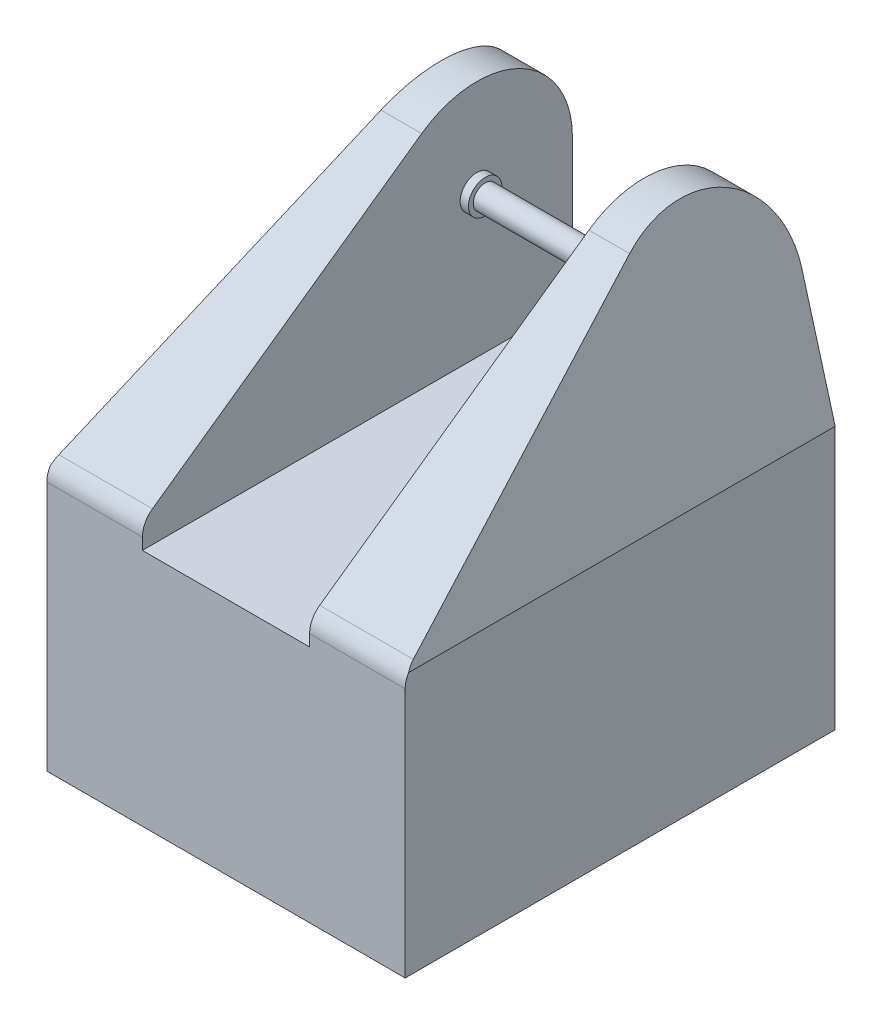
SolidWorks part; units mm, degrees
ref_plane "前基準面" through (0, 0, 0) normal (0, 0, 1) x (1, 0, 0)
ref_plane "上基準面" through (0, 0, 0) normal (0, 1, 0) x (1, 0, 0)
ref_plane "右基準面" through (0, 0, 0) normal (1, 0, 0) x (0, 0, -1)
sketch "草圖1" plane through (0, 0, 0) normal (1, 0, 0) x (0, 0, -1)
  line L4 (0, 0) -> (0, 160)
  line L5 (-63.0931, 192.6605) -> (-180, 110)
  line L6 (-180, 110) -> (-180, 0)
  line L7 (-180, 0) -> (0, 0)
  line L8 (-40, 200) -> (39.9971, 200) construction
  arc A0 (-63.0931, 192.6605) -> (0, 160) centre (-40, 160) cw
  point P7 (0, 237.2713)
  dimension "D4" = 40
  dimension "D1" = 200
  dimension "D2" = 110
  dimension "D3" = 180
extrude "填料-伸長1" add sketch "草圖1" along normal blind 150
fillet "圓角1" radius 10 1 edges at (75, 110, 180)
sketch "草圖2" plane through (0, 0, 0) normal (0, 0, -1) x (-1, 0, 0)
  line L0 (-150, 160) -> (0, 160) construction
  line L5 (-150, 110) -> (-125, 200)
  line L6 (-150, 0) -> (-150, 160) construction
  line L7 (-150, 0) -> (0, 0) construction
  line L8 (-110, 110) -> (-110, 202.9168)
  line L9 (-110, 202.9168) -> (-40, 202.9168)
  line L10 (-40, 202.9168) -> (-40, 110)
  line L11 (0, 200) -> (-150, 200) construction
  line L12 (-125, 200) -> (-125, 212.3172)
  line L13 (-125, 212.3172) -> (-176.077, 212.3172)
  line L14 (-176.077, 212.3172) -> (-176.077, 111.4072)
  line L15 (-176.077, 111.4072) -> (-150, 110)
  line L16 (-75, 160) -> (-75, 51.1238) construction
  line L17 (26.077, 111.4072) -> (0, 110)
  line L18 (26.077, 212.3172) -> (26.077, 111.4072)
  line L19 (-25, 212.3172) -> (26.077, 212.3172)
  line L20 (-25, 200) -> (-25, 212.3172)
  line L21 (0, 110) -> (-25, 200)
  line L22 (-110, 110) -> (-110, 100)
  line L23 (-110, 100) -> (-40, 100)
  line L24 (-40, 100) -> (-40, 110)
  point P0 (-75, 160)
  dimension "D1" = 70
  dimension "D2" = 100
  dimension "D3" = 15
  dimension "D4" = 35
extrude "除料-伸長1" cut sketch "草圖2" against normal through all
sketch "Sketch1" plane through (0, 0, 0) normal (0, -1, 0) x (1, 0, 0)
  line L1 (150, 0) -> (0, 0) construction
  circle A0 centre (75, 40) radius 12.5
  dimension "D2" = 25
  dimension "D1" = 40
extrude "Cut-Extrude1" cut sketch "Sketch1" against normal blind 10
sketch "Sketch2" plane through (40, 0, 0) normal (1, 0, 0) x (0, 0, -1)
  circle A0 centre (-40, 160) radius 5
extrude "Cut-Extrude2" cut sketch "Sketch2" against normal blind 10 and the other way blind 80
sketch "Sketch4" plane through (0, 0, 0) normal (0, -1, 0) x (1, 0, 0)
  circle A0 centre (75, 40) radius 11.405
  circle A1 centre (75, 40) radius 12.5
  dimension "D1" = 22.81
extrude "Boss-Extrude1" add sketch "Sketch4" against normal up to surface (10 mm away) up to face at (75, 10, 27.5)
sketch "Sketch8" plane through (120, 0, 0) normal (-1, 0, 0) x (0, 0, 1)
  circle A0 centre (40, 160) radius 5
extrude "Boss-Extrude3" add sketch "Sketch8" along normal up to surface (90 mm away) up to face at (30, 165, 40)
sketch "Sketch9" plane through (110, 0, 0) normal (-1, 0, 0) x (0, 0, 1)
  circle A0 centre (40, 160) radius 5
  circle A1 centre (40, 160) radius 7
  dimension "D1" = 14
extrude "Boss-Extrude4" add sketch "Sketch9" along normal blind 3.5
sketch "Sketch10" plane through (40, 0, 0) normal (1, 0, 0) x (0, 0, -1)
  circle A0 centre (-40, 160) radius 5
  circle A1 centre (-40, 160) radius 7
  dimension "D1" = 14
extrude "Boss-Extrude5" add sketch "Sketch10" along normal blind 3.5
sketch "Sketch11" plane through (106.5, 0, 0) normal (-1, 0, 0) x (0, 0, 1)
  circle A0 centre (40, 160) radius 7
